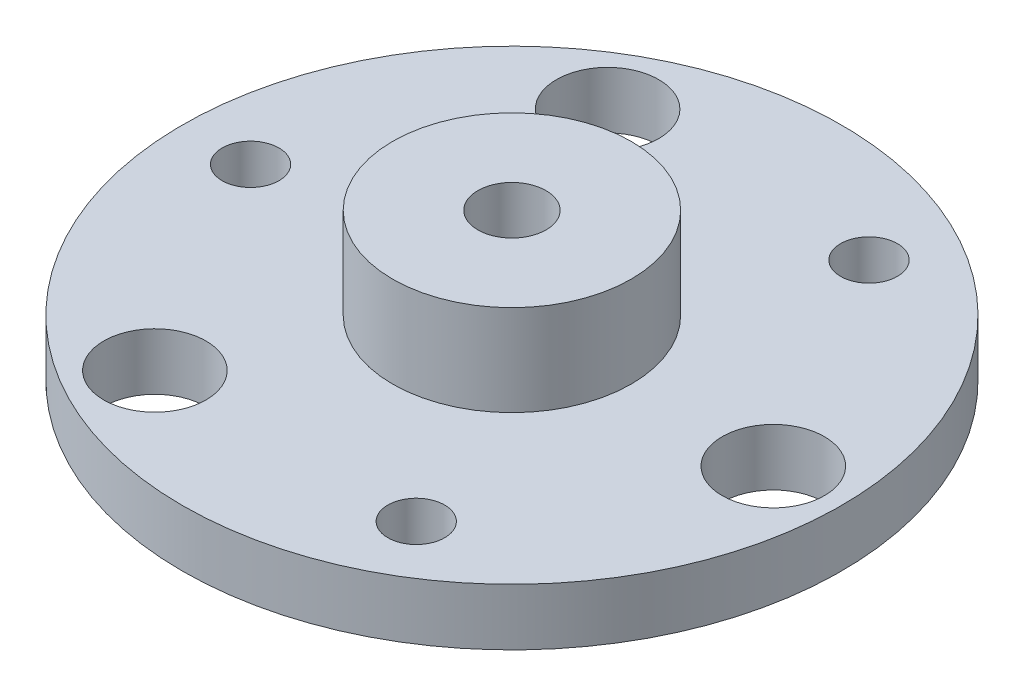
SolidWorks part; units mm, degrees
ref_plane "Front Plane" through (0, 0, 0) normal (0, 0, 1) x (1, 0, 0)
ref_plane "Top Plane" through (0, 0, 0) normal (0, 1, 0) x (1, 0, 0)
ref_plane "Right Plane" through (0, 0, 0) normal (1, 0, 0) x (0, 0, -1)
sketch "Sketch1" plane through (0, 0, 0) normal (0, 1, 0) x (1, 0, 0)
  circle A0 centre (0, 0) radius 29
  dimension "D1" = 58
extrude "Boss-Extrude2" add sketch "Sketch1" along normal blind 5 contours A0
sketch "Sketch3" plane through (0, 5, 0) normal (0, 1, 0) x (1, 0, 0)
  circle A0 centre (0, 0) radius 10.5
  dimension "D1" = 21
extrude "Boss-Extrude3" add sketch "Sketch3" along normal blind 8 contours A0
sketch "Sketch4" plane through (0, 13, 0) normal (0, 1, 0) x (1, 0, 0)
  circle A0 centre (0, 0) radius 3
  dimension "D1" = 6
extrude "Cut-Extrude1" cut sketch "Sketch4" against normal through all
sketch "Sketch6" plane through (0, 0, 0) normal (0, -1, 0) x (1, 0, 0)
  circle A0 centre (0, 0) radius 10
  dimension "D1" = 20
extrude "Boss-Extrude5" add sketch "Sketch6" along normal blind 7
sketch "Sketch8" plane through (0, 0, 0) normal (0, 1, 0) x (1, 0, 0)
  circle A0 centre (0, 0) radius 3
  dimension "D1" = 6
extrude "Cut-Extrude3" cut sketch "Sketch8" against normal through all
sketch "Sketch9" plane through (0, 5, 0) normal (0, 1, 0) x (1, 0, 0)
  line L1 (0, 0) -> (-23, 0) construction
  circle A1 centre (11.5, 19.9186) radius 2.5
  circle A2 centre (-23, 0) radius 2.5
  circle A3 centre (11.5, -19.9186) radius 2.5
  dimension "D2" = 5
  dimension "D4" = 23
  dimension "D3" = 3
extrude "Cut-Extrude4" cut sketch "Sketch9" against normal through all
sketch "Sketch10" plane through (0, 5, 0) normal (0, 1, 0) x (1, 0, 0)
  line L0 (0, 0) -> (-11.5, -19.9186) construction
  line L1 (0, 0) -> (-23, 0) construction
  circle A0 centre (-11.5, -19.9186) radius 4.5
  circle A1 centre (-11.5, 19.9186) radius 4.5
  circle A2 centre (23, 0) radius 4.5
  dimension "D1" = 9
  dimension "D3" = 23
  dimension "D4" = 60
  dimension "D2" = 3
extrude "Cut-Extrude5" cut sketch "Sketch10" against normal through all
